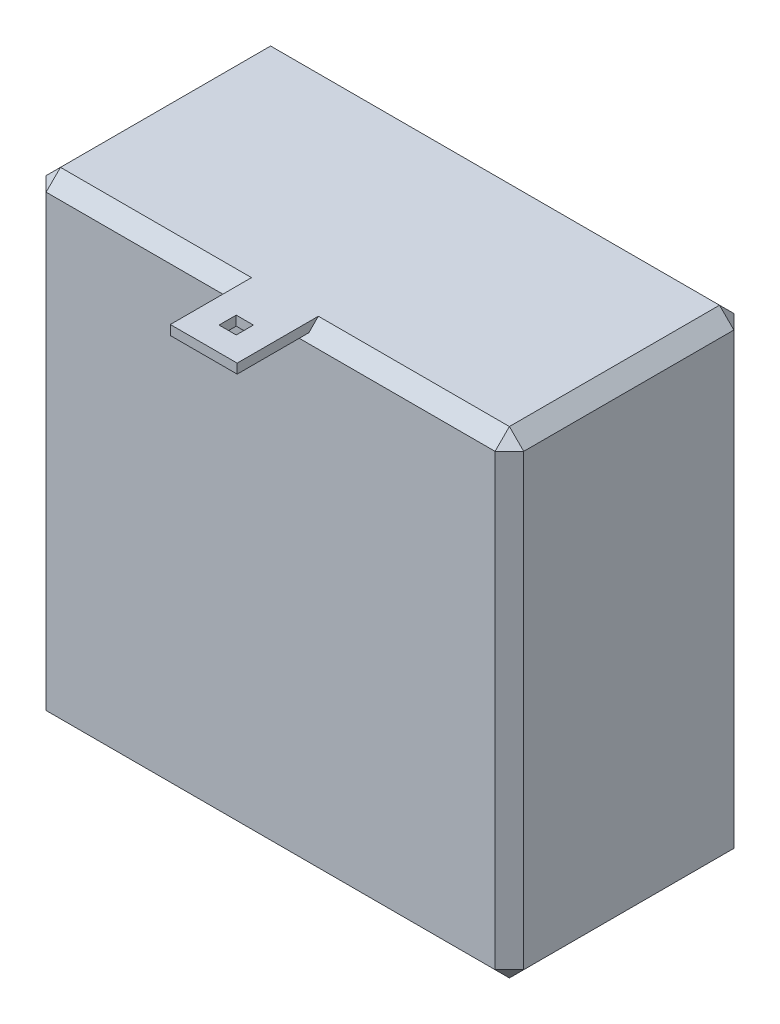
SolidWorks part; units mm, degrees
ref_plane "Front" through (0, 0, 0) normal (0, 0, 1) x (1, 0, 0)
ref_plane "Top" through (0, 0, 0) normal (0, 1, 0) x (1, 0, 0)
ref_plane "Right" through (0, 0, 0) normal (1, 0, 0) x (0, 0, -1)
sketch "Sketch1" plane through (0, 0, 0) normal (0, 0, 1) x (1, 0, 0)
  line L1 (0, 0) -> (50, 0)
  line L2 (0, 0) -> (0, 50)
  line L3 (0, 50) -> (50, 50)
  line L4 (50, 0) -> (50, 50)
  dimension "D1" = 50
extrude "Boss-Extrude1" add sketch "Sketch1" along normal blind 25
chamfer "Chamfer1" distance 1.5 angle 45 12 edges at (0, 25, 0) (0, 50, 12.5) (25, 50, 0) (50, 50, 12.5) (50, 25, 0) (0, 0, 12.5) (25, 0, 0) (50, 0, 12.5) (25, 50, 25) (50, 25, 25) (25, 0, 25) (0, 25, 25)
sketch "Sketch2" plane through (0, 0, 25) normal (0, 0, 1) x (1, 0, 0)
  line L0 (1.5, 50) -> (48.5, 50) construction
  line L1 (21.5, 50) -> (28.5, 50)
  line L2 (21.5, 50) -> (21.5, 49)
  line L3 (21.5, 49) -> (28.5, 49)
  line L4 (28.5, 50) -> (28.5, 49)
  point P6 (25, 50)
  dimension "D1" = 1
  dimension "D2" = 7
extrude "Boss-Extrude2" add sketch "Sketch2" along normal blind 7 and the other way blind 10
sketch "Sketch3" plane through (0, 49, 0) normal (0, -1, 0) x (1, 0, 0)
  line L0 (25, 32) -> (25, 29.5) construction
  line L1 (24.1, 29.5) -> (25.9, 29.5)
  line L2 (24.1, 29.5) -> (24.1, 27.7)
  line L3 (24.1, 27.7) -> (25.9, 27.7)
  line L4 (25.9, 29.5) -> (25.9, 27.7)
  line L5 (21.5, 32) -> (28.5, 32) construction
  dimension "D1" = 2.5
  dimension "D2" = 1.8
extrude "Cut-Extrude1" cut sketch "Sketch3" against normal blind 7
